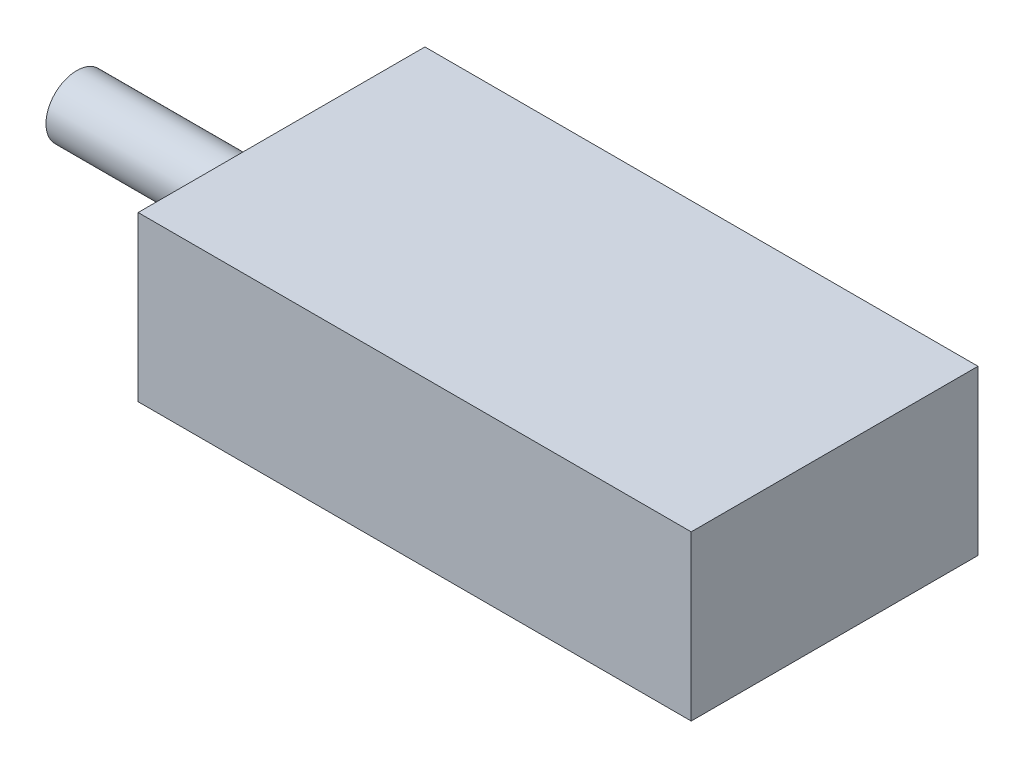
SolidWorks part; units mm, degrees
material "ABS"
ref_plane "Front Plane" through (0, 0, 0) normal (0, 0, 1) x (1, 0, 0)
ref_plane "Top Plane" through (0, 0, 0) normal (0, 1, 0) x (1, 0, 0)
ref_plane "Right Plane" through (0, 0, 0) normal (1, 0, 0) x (0, 0, -1)
other "Configuration Table"
sketch "Sketch1" plane through (0, 0, 0) normal (0, 1, 0) x (1, 0, 0)
  line L1 (-13.5, -7) -> (13.5, -7)
  line L2 (-13.5, -7) -> (-13.5, 7)
  line L3 (-13.5, 7) -> (13.5, 7)
  line L4 (13.5, -7) -> (13.5, 7)
  line L5 (-13.5, -7) -> (13.5, 7) construction
  line L6 (-13.5, 7) -> (13.5, -7) construction
  point P6 (0, 0)
  dimension "D1" = 27
  dimension "D2" = 14
extrude "Housing" add sketch "Sketch1" along normal blind 8
sketch "Sketch2" plane through (0, 0, 0) normal (1, 0, 0) x (0, 0, -1)
  circle A0 centre (0, 4) radius 1.5
  dimension "D1" = 3
extrude "Wire_Stub" add sketch "Sketch2" along normal blind 10 from offset 23.5
equation "\"Jar_OD\"= 90  'ASSUMED - Part G fallback - jar outer diameter"
equation "\"Jar_H\"= 120  'ASSUMED - Part G fallback - jar height"
equation "\"Pump_L\"= 45  'ASSUMED - Part G fallback"
equation "\"Pump_W\"= 24  'ASSUMED - Part G fallback"
equation "\"Pump_H\"= 33  'ASSUMED - Part G fallback"
equation "\"Pump_Outlet_OD\"= 7.5  'ASSUMED - Part G fallback"
equation "\"Tube_OD\"= 8  'ASSUMED - Part G fallback"
equation "\"Tube_ID\"= 6  'ASSUMED - Part G fallback"
equation "\"TDS_Body_Dia\"= 12  'ASSUMED - Part G fallback"
equation "\"TDS_Wet_Len\"= 45  'ASSUMED - Part G fallback - length in water"
equation "\"DS_Tube_Dia\"= 6  'ASSUMED - Part G fallback"
equation "\"DS_Tube_Len\"= 50  'ASSUMED - Part G fallback"
equation "\"ORP_Body_Dia\"= 12  'ASSUMED - Part G fallback"
equation "\"ORP_Body_Len\"= 150  'ASSUMED - Part G fallback"
equation "\"ORP_Cap_Dia\"= 16  'ASSUMED - Part G fallback"
equation "\"Turb_W\"= 33  'ASSUMED - Part G fallback - head width"
equation "\"Turb_D\"= 28  'ASSUMED - Part G fallback - head depth"
equation "\"Turb_H\"= 30  'ASSUMED - Part G fallback - head height"
equation "\"Turb_Slot_W\"= 10  'ASSUMED - Part G fallback - slot width"
equation "\"Flow_L\"= 62  'ASSUMED - Part G fallback YF-S201"
equation "\"Flow_W\"= 36  'ASSUMED - Part G fallback"
equation "\"Flow_H\"= 35  'ASSUMED - Part G fallback"
equation "\"Thread_G12_OD\"= 20.955  'ASSUMED - Part G fallback thread G1/2 (major diameter)"
equation "\"Valve_L\"= 75  'ASSUMED - Part G fallback"
equation "\"Valve_W\"= 45  'ASSUMED - Part G fallback"
equation "\"Valve_H\"= 60  'ASSUMED - Part G fallback"
equation "\"Tee_L\"= 40  'ASSUMED - Part G fallback - overall length"
equation "\"Tee_Branch_L\"= 25  'ASSUMED - Part G fallback"
equation "\"Tee_OD\"= 12  'ASSUMED - Part G fallback"
equation "\"Cuv_W\"= 12.5  'ASSUMED - old R3 cuvette (station suppressed in SS4)"
equation "\"Cuv_D\"= 12.5  'ASSUMED - old R3 cuvette (station suppressed in SS4)"
equation "\"Cuv_H\"= 45  'ASSUMED - old R3 cuvette (station suppressed in SS4)"
equation "\"LED_Board_L\"= 20  'ASSUMED - Part G fallback"
equation "\"LED_Board_W\"= 20  'ASSUMED - Part G fallback - LED at centre"
equation "\"GUVA_L\"= 20  'ASSUMED - Part G fallback"
equation "\"GUVA_W\"= 12  'ASSUMED - Part G fallback - sensor at centre"
equation "\"Reed_L\"= 27  'ASSUMED - Part G fallback MC-38 half"
equation "\"Reed_W\"= 14  'ASSUMED - Part G fallback"
equation "\"Reed_H\"= 8  'ASSUMED - Part G fallback"
equation "\"ESP_L\"= 51  'ASSUMED - Part G fallback"
equation "\"ESP_W\"= 28  'ASSUMED - Part G fallback"
equation "\"TFT_L\"= 58  'ASSUMED - Part G fallback - board"
equation "\"TFT_W\"= 35  'ASSUMED - Part G fallback - board"
equation "\"TFT_Win_L\"= 35  'ASSUMED - Part G fallback - visible window"
equation "\"TFT_Win_W\"= 28  'ASSUMED - Part G fallback - visible window"
equation "\"Relay_L\"= 50  'ASSUMED - Part G fallback"
equation "\"Relay_W\"= 26  'ASSUMED - Part G fallback"
equation "\"Relay_H\"= 19  'ASSUMED - Part G fallback"
equation "\"Mosfet_L\"= 34  'ASSUMED - Part G fallback"
equation "\"Mosfet_W\"= 17  'ASSUMED - Part G fallback"
equation "\"Mosfet_H\"= 12  'ASSUMED - Part G fallback"
equation "\"TDS_Board_L\"= 42  'ASSUMED - Part G fallback"
equation "\"TDS_Board_W\"= 32  'ASSUMED - Part G fallback"
equation "\"Turb_Board_L\"= 38  'ASSUMED - Part G fallback"
equation "\"Turb_Board_W\"= 28  'ASSUMED - Part G fallback"
equation "\"BNC_Thread_Dia\"= 9.5  'ASSUMED - Part G fallback"
equation "\"Plate_L\"= 420  'ASSUMED - Part G fallback"
equation "\"Plate_W\"= 297  'ASSUMED - Part G fallback"
equation "\"Plate_T\"= 6  'ASSUMED - Part G fallback"
equation "\"Probe_Clr\"= 0.3  'DESIGN VALUE - Part C rule 3 - printed probe hole = diameter + 0.3"
equation "\"Cuv_Clr\"= 0.2  'DESIGN VALUE - Part C rule 3 - cuvette pocket = size + 0.2"
equation "\"Label_H\"= 0.6  'DESIGN VALUE - Part D - raised label height"
equation "\"D1@Sketch1\" = \"Reed_L\""
equation "\"D2@Sketch1\" = \"Reed_W\""
equation "\"D1@Housing\" = \"Reed_H\""
equation "\"Booster_L\"= 150  'ASSUMED - Part G fallback - booster pump"
equation "\"Booster_W\"= 95  'ASSUMED - Part G fallback"
equation "\"Booster_H\"= 100  'ASSUMED - Part G fallback"
equation "\"PTube_OD\"= 6.35  'ASSUMED - Part G fallback - product tube 1/4 inch"
equation "\"Qz_Out\"= 12  'ASSUMED - Part G fallback - quartz channel outside square"
equation "\"Qz_Path\"= 10  'ASSUMED - Part G fallback - quartz channel inside light path"
equation "\"Qz_L\"= 40  'ASSUMED - Part G fallback - quartz channel length"
equation "\"LED860_Dia\"= 5  'ASSUMED - Part G fallback - 860 nm LED"
equation "\"BPW_L\"= 5.4  'ASSUMED - Part G fallback - BPW34"
equation "\"BPW_W\"= 4.3  'ASSUMED - Part G fallback - BPW34"
equation "\"Cart_Dia\"= 50  'ASSUMED - Part G fallback - sediment and pre-carbon cartridges"
equation "\"Cart_L\"= 255  'ASSUMED - Part G fallback"
equation "\"UF_Dia\"= 50  'ASSUMED - Part G fallback - UF cartridge"
equation "\"UF_L\"= 260  'ASSUMED - Part G fallback"
equation "\"RO_Dia\"= 62  'ASSUMED - Part G fallback - RO membrane housing"
equation "\"RO_L\"= 300  'ASSUMED - Part G fallback"
equation "\"UVC_Dia\"= 40  'ASSUMED - Part G fallback - UV-C chamber"
equation "\"UVC_L\"= 300  'ASSUMED - Part G fallback"
equation "\"Tank_W\"= 260  'ASSUMED - Part G fallback - storage tank"
equation "\"Tank_D\"= 160  'ASSUMED - Part G fallback"
equation "\"Tank_H\"= 300  'ASSUMED - Part G fallback"
equation "\"Cab_W\"= 400  'ASSUMED - Part G fallback - purifier cabinet"
equation "\"Cab_D\"= 270  'ASSUMED - Part G fallback"
equation "\"Cab_H\"= 560  'ASSUMED - Part G fallback"
equation "\"ORP_Board_L\"= 40  'ASSUMED - Part G fallback - ORP buffer board"
equation "\"ORP_Board_W\"= 30  'ASSUMED - Part G fallback"
equation "\"Opt_Board_L\"= 50  'ASSUMED - Part G fallback - optical front-end board"
equation "\"Opt_Board_W\"= 40  'ASSUMED - Part G fallback"
equation "\"Buck_L\"= 43  'ASSUMED - Part G fallback - 12 V to 5 V buck module"
equation "\"Buck_W\"= 21  'ASSUMED - Part G fallback"
equation "\"Buck_H\"= 14  'ASSUMED - Part G fallback"
equation "\"BB_L\"= 165  'ASSUMED - Part G fallback - breadboard (As_Built_R3 only)"
equation "\"BB_W\"= 55  'ASSUMED - Part G fallback"
equation "\"BB_H\"= 10  'ASSUMED - Part G fallback"
